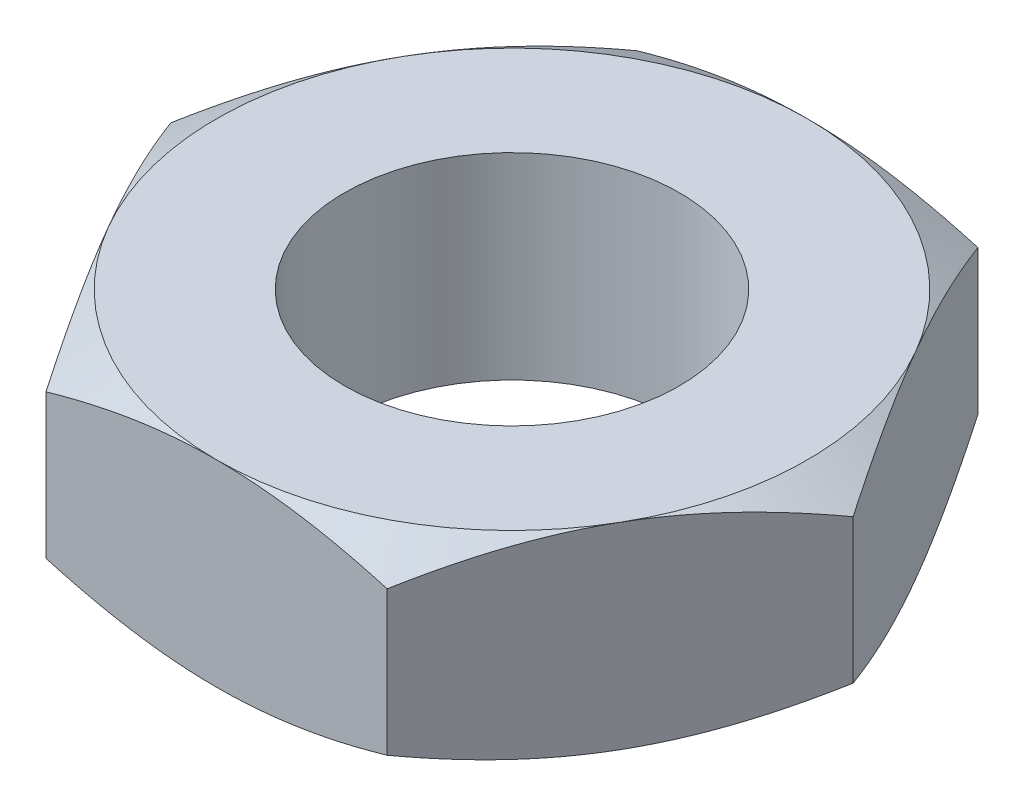
SolidWorks part; units mm, degrees
material "Chrome Stainless Steel"
ref_plane "Front Plane" through (0, 0, 0) normal (0, 0, 1) x (1, 0, 0)
ref_plane "Top Plane" through (0, 0, 0) normal (0, 1, 0) x (1, 0, 0)
ref_plane "Right Plane" through (0, 0, 0) normal (1, 0, 0) x (0, 0, -1)
sketch "Sketch1" plane through (0, 0, 0) normal (0, 1, 0) x (1, 0, 0)
  line L1 (10.3923, 0) -> (5.1962, 9)
  line L2 (5.1962, 9) -> (-5.1962, 9)
  line L3 (-5.1962, 9) -> (-10.3923, 0)
  line L4 (-10.3923, 0) -> (-5.1962, -9)
  line L5 (-5.1962, -9) -> (5.1962, -9)
  line L6 (5.1962, -9) -> (10.3923, 0)
  circle A0 centre (0, 0) radius 9 construction
  dimension "D1" = 18
extrude "Boss-Extrude1" add sketch "Sketch1" along normal mid plane 6
sketch "Sketch2" plane through (0, 0, 0) normal (1, 0, 0) x (0, 0, -1)
  line L0 (0, 0) -> (0, -50000) construction
  line L1 (9, 3) -> (13.8136, 3)
  line L2 (13.8136, 3) -> (13.8136, 0.2209)
  line L3 (13.8136, 0.2209) -> (9, 3)
  dimension "D1" = 30
revolve "Cut-Revolve1" cut sketch "Sketch2" angle 360 about L0
mirror "Mirror1" about plane through (0, 0, 0) normal (0, 1, 0) of "Cut-Revolve1"
hole_wizard "M12x1.75 Tapped Hole1" positions "Sketch3" profile "Sketch4" tap size "M12x1.75" standard "ANSI Metric" end condition up to next
sketch "Sketch3" plane through (0, 3, 0) normal (0, 1, 0) x (1, 0, 0)
  point P0 (0, 0)
sketch "Sketch4" plane through (0, 3, 0) normal (1, 0, 0) x (0, 0, 1)
  line L0 (0, 0) -> (0, 6)
  line L1 (0, 6) -> (5.1, 6)
  line L2 (5.1, 6) -> (5.1, 0)
  line L5 (5.1, 0) -> (0, 0)
  line L11 (0, -6.35) -> (0, 107.95) construction
  dimension "Thru Tap Drill Dia." = 10.2
  dimension "Thru Tap Drill Depth" = 6
cosmetic thread "Hole Thread1" parameters "D2"=12
